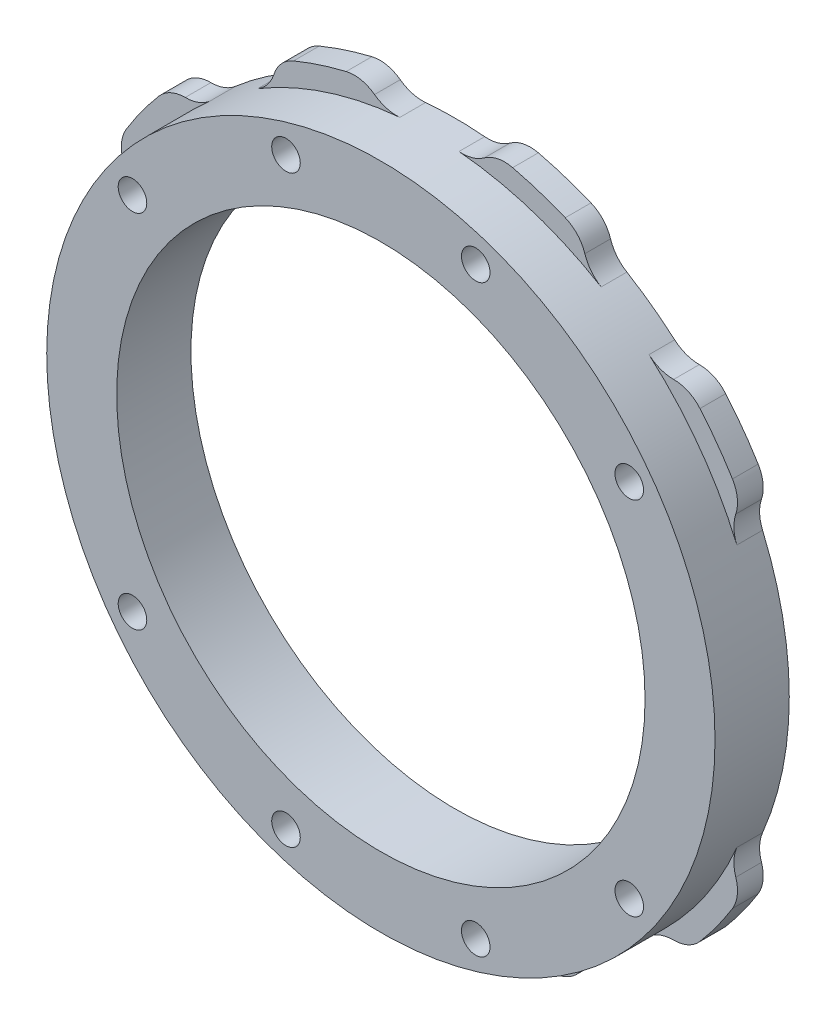
SolidWorks part; units mm, degrees
material "2014 Legierung"
ref_plane "Vorne" through (0, 0, 0) normal (0, 0, 1) x (1, 0, 0)
ref_plane "Oben" through (0, 0, 0) normal (0, 1, 0) x (1, 0, 0)
ref_plane "Rechts" through (0, 0, 0) normal (1, 0, 0) x (0, 0, -1)
sketch "Skizze1" plane through (0, 0, 0) normal (0, 0, 1) x (1, 0, 0)
  line L0 (3.9109, 24.6922) -> (3.6762, 23.2107) construction
  line L1 (0, 0) -> (0, 46.5) construction
  line L2 (-7.2742, 45.9275) -> (0, 0) construction
  line L3 (0, 0) -> (-10.9794, 21.5483) construction
  line L4 (-6.6439, 20.4477) -> (0, 0) construction
  arc A0 (15.4399, 17.7161) -> (17.1008, 17.1008) centre (17.0825, 19.6007) ccw construction
  arc A1 (17.1008, 17.1008) -> (19.0213, 16.2232) centre (17.1191, 14.6009) cw construction
  circle A2 centre (2.299, 25.8982) radius 2.5 construction
  circle A3 centre (5.2675, 21.8747) radius 2.5 construction
  arc A4 (2.0779, 23.408) -> (3.7832, 23.8864) centre (2.299, 25.8982) ccw construction
  arc A5 (3.7832, 23.8864) -> (5.8528, 24.3052) centre (5.2675, 21.8747) cw construction
  arc A6 (-2.0779, 23.408) -> (-3.7832, 23.8864) centre (-2.299, 25.8982) cw construction
  arc A7 (-3.7832, 23.8864) -> (-5.8528, 24.3052) centre (-5.2675, 21.8747) ccw construction
  arc A8 (12.0778, 20.1588) -> (10.9794, 21.5483) centre (13.3626, 22.3034) cw construction
  arc A9 (10.9794, 21.5483) -> (9.5513, 23.1035) centre (8.5962, 20.7932) ccw construction
  arc A10 (15.4399, 17.7161) -> (12.0778, 20.1588) centre (0, 0) ccw construction
  arc A11 (-22.9044, 5.2572) -> (-22.9044, -5.2572) centre (0, 0) ccw construction
  arc A12 (22.9044, 5.2572) -> (22.9044, -5.2572) centre (0, 0) cw construction
  arc A13 (21.6202, 9.2097) -> (21.5483, 10.9794) centre (23.9202, 10.1894) cw construction
  arc A14 (21.5483, 10.9794) -> (21.3071, 13.077) centre (19.1764, 11.7693) ccw construction
  arc A15 (22.9044, 5.2572) -> (21.6202, 9.2097) centre (0, 0) ccw construction
  arc A16 (21.6202, -9.2097) -> (21.5483, -10.9794) centre (23.9202, -10.1894) ccw construction
  arc A17 (21.5483, -10.9794) -> (21.3071, -13.077) centre (19.1764, -11.7693) cw construction
  arc A18 (-22.8069, 5.2348) -> (-22.8069, -5.2348) centre (0, 0) ccw
  arc A19 (-22.8069, -5.2348) -> (-21.5282, -9.1705) centre (0, 0) ccw
  arc A20 (21.6202, -9.2097) -> (22.9044, -5.2572) centre (0, 0) ccw construction
  arc A21 (12.0778, -20.1588) -> (10.9794, -21.5483) centre (13.3626, -22.3034) ccw construction
  arc A22 (10.9794, -21.5483) -> (9.5513, -23.1035) centre (8.5962, -20.7932) cw construction
  arc A23 (15.4399, -17.7161) -> (17.1008, -17.1008) centre (17.0825, -19.6007) cw construction
  arc A24 (17.1008, -17.1008) -> (19.0213, -16.2232) centre (17.1191, -14.6009) ccw construction
  arc A25 (12.0778, -20.1588) -> (15.4399, -17.7161) centre (0, 0) ccw construction
  arc A26 (-2.0779, -23.408) -> (-3.7832, -23.8864) centre (-2.299, -25.8982) ccw construction
  arc A27 (-3.7832, -23.8864) -> (-5.8528, -24.3052) centre (-5.2675, -21.8747) cw construction
  arc A28 (2.0779, -23.408) -> (3.7832, -23.8864) centre (2.299, -25.8982) cw construction
  arc A29 (3.7832, -23.8864) -> (5.8528, -24.3052) centre (5.2675, -21.8747) ccw construction
  arc A30 (-2.0779, -23.408) -> (2.0779, -23.408) centre (0, 0) ccw construction
  arc A31 (-15.4399, -17.7161) -> (-17.1008, -17.1008) centre (-17.0825, -19.6007) ccw construction
  arc A32 (-17.1008, -17.1008) -> (-19.0213, -16.2232) centre (-17.1191, -14.6009) cw construction
  arc A33 (-12.0778, -20.1588) -> (-10.9794, -21.5483) centre (-13.3626, -22.3034) cw construction
  arc A34 (-10.9794, -21.5483) -> (-9.5513, -23.1035) centre (-8.5962, -20.7932) ccw construction
  arc A35 (-15.4399, -17.7161) -> (-12.0778, -20.1588) centre (0, 0) ccw construction
  arc A36 (-21.5282, -9.1705) -> (-21.4534, -11.011) centre (-23.9202, -10.1894) cw
  arc A37 (-21.4534, -11.011) -> (-21.2218, -13.0247) centre (-19.1764, -11.7693) ccw
  arc A38 (-21.6202, -9.2097) -> (-21.5483, -10.9794) centre (-23.9202, -10.1894) cw construction
  arc A39 (-21.5483, -10.9794) -> (-21.3071, -13.077) centre (-19.1764, -11.7693) ccw construction
  arc A40 (-22.9044, -5.2572) -> (-21.6202, -9.2097) centre (0, 0) ccw construction
  arc A41 (-21.6202, 9.2097) -> (-21.5483, 10.9794) centre (-23.9202, 10.1894) ccw construction
  arc A42 (-21.5483, 10.9794) -> (-21.3071, 13.077) centre (-19.1764, 11.7693) cw construction
  arc A43 (-21.2218, -13.0247) -> (-18.9452, -16.1583) centre (0, 0) ccw
  arc A44 (-17.1015, -17.0008) -> (-18.9452, -16.1583) centre (-17.1191, -14.6009) cw
  arc A45 (-21.6202, 9.2097) -> (-22.9044, 5.2572) centre (0, 0) ccw construction
  arc A46 (-12.0778, 20.1588) -> (-10.9794, 21.5483) centre (-13.3626, 22.3034) ccw construction
  arc A47 (-10.9794, 21.5483) -> (-9.5513, 23.1035) centre (-8.5962, 20.7932) cw construction
  arc A48 (-15.4399, 17.7161) -> (-17.1008, 17.1008) centre (-17.0825, 19.6007) cw construction
  arc A49 (-17.1008, 17.1008) -> (-19.0213, 16.2232) centre (-17.1191, 14.6009) ccw construction
  arc A50 (-12.0778, 20.1588) -> (-15.4399, 17.7161) centre (0, 0) ccw construction
  arc A51 (-19.0213, 16.2232) -> (-21.3071, 13.077) centre (0, 0) ccw construction
  arc A52 (-5.8528, 24.3052) -> (-9.5513, 23.1035) centre (0, 0) ccw construction
  arc A53 (-15.3742, -17.6407) -> (-17.1015, -17.0008) centre (-17.0825, -19.6007) ccw
  arc A54 (9.5513, 23.1035) -> (5.8528, 24.3052) centre (0, 0) ccw construction
  arc A55 (21.3071, 13.077) -> (19.0213, 16.2232) centre (0, 0) ccw construction
  arc A56 (-21.3071, -13.077) -> (-19.0213, -16.2232) centre (0, 0) ccw construction
  arc A57 (-9.5513, -23.1035) -> (-5.8528, -24.3052) centre (0, 0) ccw construction
  arc A58 (5.8528, -24.3052) -> (9.5513, -23.1035) centre (0, 0) ccw construction
  arc A59 (19.0213, -16.2232) -> (21.3071, -13.077) centre (0, 0) ccw construction
  arc A60 (-15.3742, -17.6407) -> (-12.0264, -20.073) centre (0, 0) ccw
  arc A61 (-12.0264, -20.073) -> (-10.8841, -21.5181) centre (-13.3626, -22.3034) cw
  arc A62 (-10.8841, -21.5181) -> (-9.5131, -23.0111) centre (-8.5962, -20.7932) ccw
  arc A63 (-9.5131, -23.0111) -> (-5.8294, -24.208) centre (0, 0) ccw
  arc A64 (-3.8426, -23.806) -> (-5.8294, -24.208) centre (-5.2675, -21.8747) cw
  arc A65 (-2.0691, -23.3083) -> (-3.8426, -23.806) centre (-2.299, -25.8982) ccw
  arc A66 (-2.0691, -23.3083) -> (2.0691, -23.3083) centre (0, 0) ccw
  arc A67 (2.0691, -23.3083) -> (3.8426, -23.806) centre (2.299, -25.8982) cw
  arc A68 (3.8426, -23.806) -> (5.8294, -24.208) centre (5.2675, -21.8747) ccw
  arc A69 (5.8294, -24.208) -> (9.5131, -23.0111) centre (0, 0) ccw
  arc A70 (10.8841, -21.5181) -> (9.5131, -23.0111) centre (8.5962, -20.7932) cw
  arc A71 (12.0264, -20.073) -> (10.8841, -21.5181) centre (13.3626, -22.3034) ccw
  arc A72 (12.0264, -20.073) -> (15.3742, -17.6407) centre (0, 0) ccw
  arc A73 (15.3742, -17.6407) -> (17.1015, -17.0008) centre (17.0825, -19.6007) cw
  arc A74 (17.1015, -17.0008) -> (18.9452, -16.1583) centre (17.1191, -14.6009) ccw
  arc A75 (18.9452, -16.1583) -> (21.2218, -13.0247) centre (0, 0) ccw
  arc A76 (2.0779, 23.408) -> (-2.0779, 23.408) centre (0, 0) ccw construction
  arc A77 (21.4534, -11.011) -> (21.2218, -13.0247) centre (19.1764, -11.7693) cw
  arc A78 (21.5282, -9.1705) -> (21.4534, -11.011) centre (23.9202, -10.1894) ccw
  arc A79 (21.5282, -9.1705) -> (22.8069, -5.2348) centre (0, 0) ccw
  arc A80 (22.8069, 5.2348) -> (22.8069, -5.2348) centre (0, 0) cw
  arc A81 (22.8069, 5.2348) -> (21.5282, 9.1705) centre (0, 0) ccw
  arc A82 (21.5282, 9.1705) -> (21.4534, 11.011) centre (23.9202, 10.1894) cw
  arc A83 (21.4534, 11.011) -> (21.2218, 13.0247) centre (19.1764, 11.7693) ccw
  arc A84 (21.2218, 13.0247) -> (18.9452, 16.1583) centre (0, 0) ccw
  arc A85 (17.1015, 17.0008) -> (18.9452, 16.1583) centre (17.1191, 14.6009) cw
  arc A86 (15.3742, 17.6407) -> (17.1015, 17.0008) centre (17.0825, 19.6007) ccw
  arc A87 (15.3742, 17.6407) -> (12.0264, 20.073) centre (0, 0) ccw
  arc A88 (12.0264, 20.073) -> (10.8841, 21.5181) centre (13.3626, 22.3034) cw
  arc A89 (10.8841, 21.5181) -> (9.5131, 23.0111) centre (8.5962, 20.7932) ccw
  arc A90 (9.5131, 23.0111) -> (5.8294, 24.208) centre (0, 0) ccw
  arc A91 (3.8426, 23.806) -> (5.8294, 24.208) centre (5.2675, 21.8747) cw
  arc A92 (2.0691, 23.3083) -> (3.8426, 23.806) centre (2.299, 25.8982) ccw
  arc A93 (2.0691, 23.3083) -> (-2.0691, 23.3083) centre (0, 0) ccw
  arc A94 (-2.0691, 23.3083) -> (-3.8426, 23.806) centre (-2.299, 25.8982) cw
  arc A95 (-3.8426, 23.806) -> (-5.8294, 24.208) centre (-5.2675, 21.8747) ccw
  arc A96 (-5.8294, 24.208) -> (-9.5131, 23.0111) centre (0, 0) ccw
  arc A97 (-10.8841, 21.5181) -> (-9.5131, 23.0111) centre (-8.5962, 20.7932) cw
  arc A98 (-12.0264, 20.073) -> (-10.8841, 21.5181) centre (-13.3626, 22.3034) ccw
  arc A99 (-12.0264, 20.073) -> (-15.3742, 17.6407) centre (0, 0) ccw
  arc A100 (-15.3742, 17.6407) -> (-17.1015, 17.0008) centre (-17.0825, 19.6007) cw
  arc A101 (-17.1015, 17.0008) -> (-18.9452, 16.1583) centre (-17.1191, 14.6009) ccw
  arc A102 (-18.9452, 16.1583) -> (-21.2218, 13.0247) centre (0, 0) ccw
  arc A103 (-21.4534, 11.011) -> (-21.2218, 13.0247) centre (-19.1764, 11.7693) cw
  arc A104 (-21.5282, 9.1705) -> (-21.4534, 11.011) centre (-23.9202, 10.1894) ccw
  arc A105 (-21.5282, 9.1705) -> (-22.8069, 5.2348) centre (0, 0) ccw
  circle A106 centre (0, 0) radius 18.5
  circle A107 centre (-6.6439, 20.4477) radius 1 construction
  circle A108 centre (-6.6439, 20.4477) radius 2 construction
  circle A110 centre (0, 0) radius 23.5 construction
  arc A113 (-22.9044, -5.2572) -> (-23.8864, -3.7832) centre (-25.341, -5.8165) ccw [skipped]
  arc A114 (-23.8864, -3.7832) -> (-24.9243, -1.9444) centre (-22.4318, -1.75) cw [skipped]
  arc A115 (-22.9044, 5.2572) -> (-23.8864, 3.7832) centre (-25.341, 5.8165) cw [skipped]
  arc A116 (-23.8864, 3.7832) -> (-24.9243, 1.9444) centre (-22.4318, 1.75) ccw [skipped]
  arc A117 (22.9044, 5.2572) -> (23.8864, 3.7832) centre (25.341, 5.8165) ccw [skipped]
  arc A118 (23.8864, 3.7832) -> (24.9243, 1.9444) centre (22.4318, 1.75) cw [skipped]
  arc A119 (22.9044, -5.2572) -> (23.8864, -3.7832) centre (25.341, -5.8165) cw [skipped]
  arc A120 (23.8864, -3.7832) -> (24.9243, -1.9444) centre (22.4318, -1.75) ccw [skipped]
  point P3 (-23.8864, -3.7832)
  point P13 (3.7832, 23.8864)
  point P24 (23.8864, 3.7832)
  point P27 (17.1008, 17.1008)
  point P51 (21.5483, -10.9794)
  point P63 (10.9794, -21.5483)
  point P75 (-3.7832, -23.8864)
  point P87 (-17.1008, -17.1008)
  point P111 (-21.5483, 10.9794)
  point P123 (-10.9794, 21.5483)
  dimension "D1" = 25
  dimension "D4" = 5
  dimension "D5" = 0.1
  dimension "D7" = 4
  dimension "D8" = 2
  dimension "D9" = 37
  dimension "D12" = 23.4
  dimension "D3" = 18
  dimension "D6" = 18
  dimension "D10" = 18
  dimension "D11" = 21.5
extrude "Linear austragen1" add sketch "Skizze1" along normal blind 1.8
sketch "Skizze2" plane through (0, 0, 1.8) normal (0, 0, 1) x (1, 0, 0)
  circle A0 centre (0, 0) radius 18.5
  circle A1 centre (0, 0) radius 23.4
  arc A2 (2.0691, 23.3083) -> (-2.0691, 23.3083) centre (0, 0) ccw construction
  circle A3 centre (0, 0) radius 18.5 construction
extrude "Linear austragen2" add sketch "Skizze2" along normal blind 3.4
sketch "Skizze3" plane through (0, 0, 5.2) normal (0, 0, 1) x (1, 0, 0)
  circle A0 centre (-6.6439, 20.4477) radius 1
  circle A1 centre (-6.6439, 20.4477) radius 1 construction
  circle A2 centre (6.6439, 20.4477) radius 1
  circle A3 centre (17.3939, 12.6374) radius 1
  circle A5 centre (17.3939, -12.6374) radius 1
  circle A6 centre (6.6439, -20.4477) radius 1
  circle A7 centre (-6.6439, -20.4477) radius 1
  circle A8 centre (-17.3939, -12.6374) radius 1
  circle A10 centre (-17.3939, 12.6374) radius 1
  circle A11 centre (21.5, 0) radius 1 [skipped]
  circle A12 centre (-21.5, 0) radius 1 [skipped]
  dimension "D1" = 10
extrude "Schnitt-Linear austragen1" cut sketch "Skizze3" against normal through all
chamfer "Chamfer1" distance 1.4 angle 45 8 edges at (18.3939, 12.6374, 0) (7.6439, 20.4477, 0) (-5.6439, 20.4477, 0) (-16.3939, 12.6374, 0) (-16.3939, -12.6374, 0) (18.3939, -12.6374, 0) (7.6439, -20.4477, 0) (-5.6439, -20.4477, 0)
